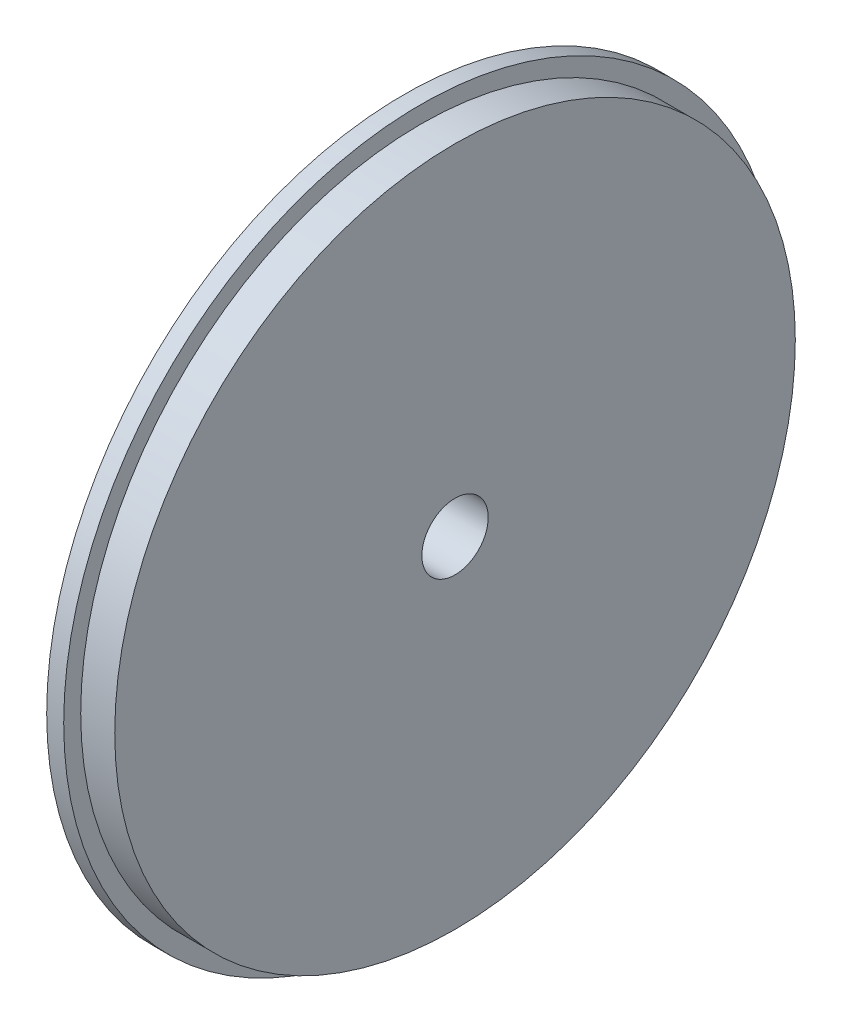
SolidWorks part; units mm, degrees
ref_plane "Front Plane" through (0, 0, 0) normal (0, 0, 1) x (1, 0, 0)
ref_plane "Top Plane" through (0, 0, 0) normal (0, 1, 0) x (1, 0, 0)
ref_plane "Right Plane" through (0, 0, 0) normal (1, 0, 0) x (0, 0, -1)
sketch "Sketch1" plane through (0, 0, 0) normal (0, 0, 1) x (1, 0, 0)
  line L0 (-0.75, 10.5) -> (-0.25, 10.5)
  line L1 (-0.75, 10.5) -> (0.75, 10.5) construction
  line L2 (-0.75, 10.5) -> (-0.75, 0) construction
  line L3 (-0.75, 0) -> (0.75, 0) construction
  line L4 (0.75, 10.5) -> (0.75, 0) construction
  line L5 (-0.75, 0.975) -> (0.75, 0.975)
  line L6 (-0.75, 0.975) -> (-0.75, 10.5)
  line L8 (0.75, 0.975) -> (0.75, 10)
  line L9 (-0.25, 10.5) -> (-0.25, 10)
  line L10 (-0.25, 10) -> (0.75, 10)
  dimension "D1" = 10.5
  dimension "D2" = 1.5
  dimension "D3" = 0.975
  dimension "D4" = 10
  dimension "D5" = 0.5
revolve "Revolve1" add sketch "Sketch1" angle 360 about L3
